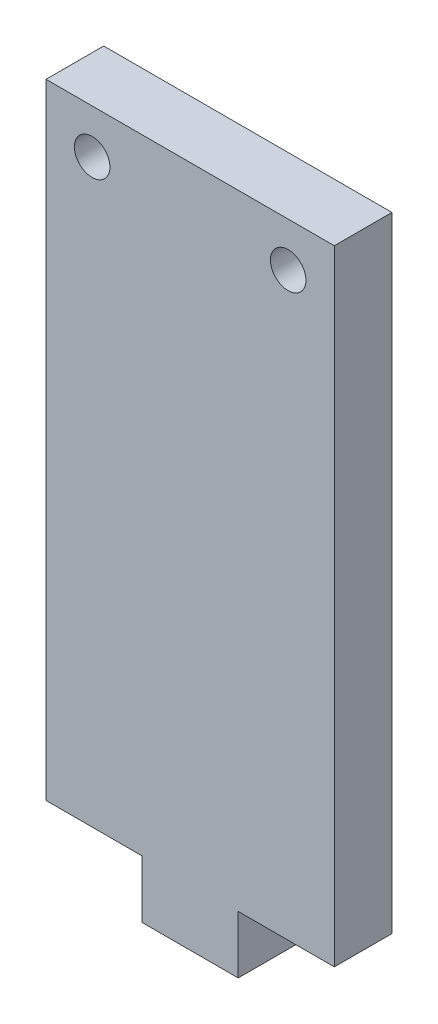
SolidWorks part; units mm, degrees
ref_plane "Plan de face" through (0, 0, 0) normal (0, 0, 1) x (1, 0, 0)
ref_plane "Plan de dessus" through (0, 0, 0) normal (0, 1, 0) x (1, 0, 0)
ref_plane "Plan de droite" through (0, 0, 0) normal (1, 0, 0) x (0, 0, -1)
sketch "Esquisse1" plane through (0, 0, 0) normal (0, 0, 1) x (1, 0, 0)
  line L1 (0, 0) -> (-30, 0)
  line L2 (0, 0) -> (0, 71)
  line L3 (0, 71) -> (-30, 71)
  line L4 (-30, 0) -> (-30, 71)
  dimension "D1" = 71
  dimension "D2" = 30
extrude "Boss.-Extru.1" add sketch "Esquisse1" along normal blind 6
sketch "Esquisse3" plane through (0, 0, 0) normal (0, 0, -1) x (-1, 0, 0)
  line L0 (0, 71) -> (30, 71) construction
  line L1 (0, 0) -> (10, 0)
  line L2 (0, 0) -> (0, 6)
  line L3 (0, 6) -> (10, 6)
  line L4 (10, 0) -> (10, 6)
  line L5 (30, 0) -> (20, 0)
  line L6 (30, 0) -> (30, 6)
  line L7 (30, 6) -> (20, 6)
  line L8 (20, 0) -> (20, 6)
  line L9 (0, 0) -> (0, 71) construction
  line L10 (30, 71) -> (30, 0) construction
  circle A0 centre (4.8, 66.4) radius 1.85
  circle A1 centre (25.2, 66.4) radius 1.85
  dimension "D5" = 3.7
  dimension "D6" = 3.7
  dimension "D1" = 10
  dimension "D2" = 10
  dimension "D3" = 6
  dimension "D4" = 6
  dimension "D7" = 4.6
  dimension "D8" = 4.8
  dimension "D9" = 4.6
  dimension "D10" = 4.8
extrude "Enlèv. mat.-Extru.1" cut sketch "Esquisse3" against normal blind 6
